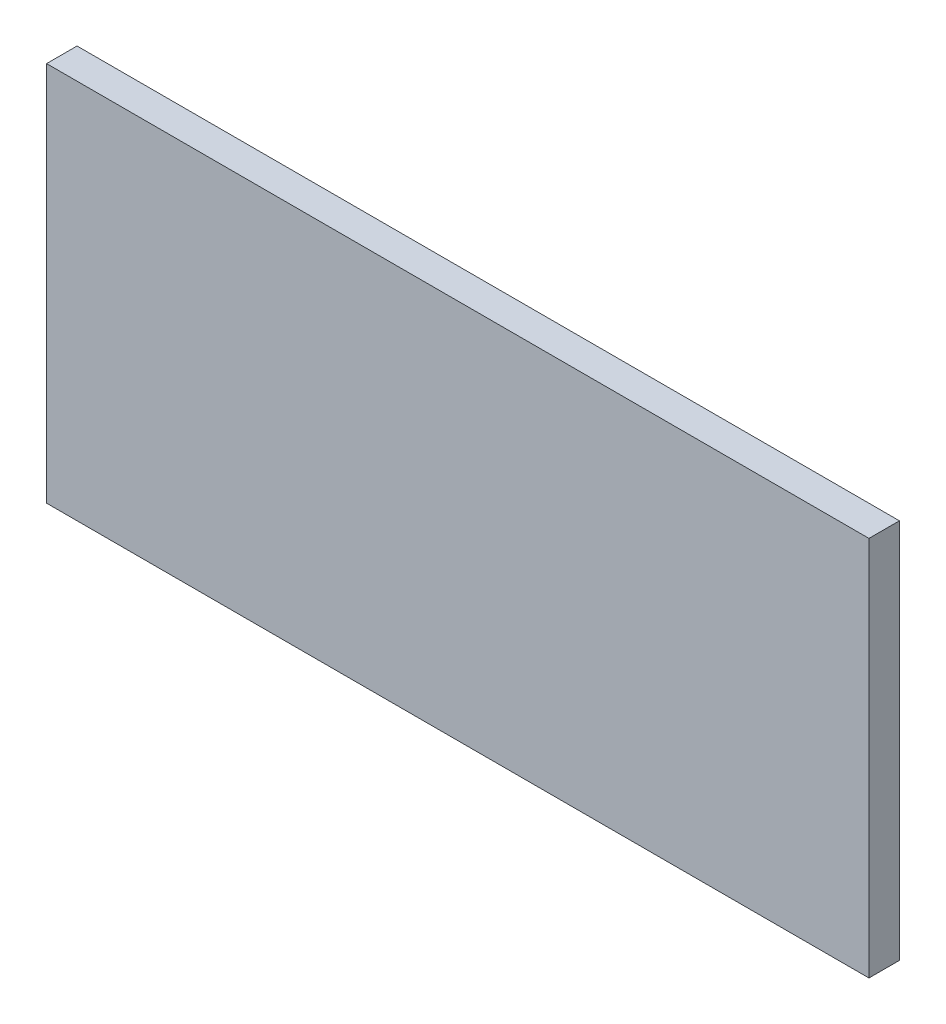
SolidWorks part; units mm, degrees
ref_plane "Front Plane" through (0, 0, 0) normal (0, 0, 1) x (1, 0, 0)
ref_plane "Top Plane" through (0, 0, 0) normal (0, 1, 0) x (1, 0, 0)
ref_plane "Right Plane" through (0, 0, 0) normal (1, 0, 0) x (0, 0, -1)
sketch "Sketch1" plane through (0, 0, 0) normal (0, 0, 1) x (1, 0, 0)
  line L1 (-270, -125) -> (270, -125)
  line L2 (-270, -125) -> (-270, 125)
  line L3 (-270, 125) -> (270, 125)
  line L4 (270, -125) -> (270, 125)
  line L5 (-270, -125) -> (270, 125) construction
  line L6 (-270, 125) -> (270, -125) construction
  point P0 (0, 0)
  dimension "D1" = 250
  dimension "D2" = 540
extrude "Boss-Extrude1" add sketch "Sketch1" along normal blind 20
